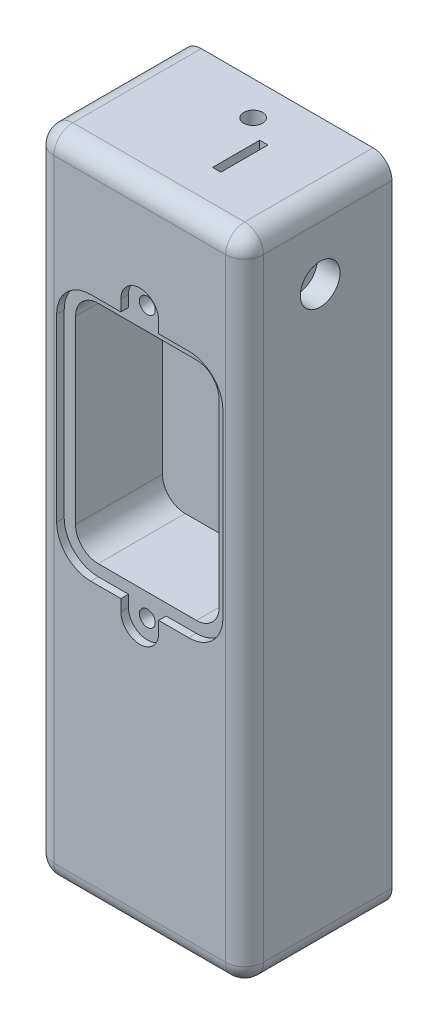
SolidWorks part; units mm, degrees
ref_plane "Plan de face" through (0, 0, 0) normal (0, 0, 1) x (1, 0, 0)
ref_plane "Plan de dessus" through (0, 0, 0) normal (0, 1, 0) x (1, 0, 0)
ref_plane "Plan de droite" through (0, 0, 0) normal (1, 0, 0) x (0, 0, -1)
sketch "Esquisse1" plane through (0, 0, 0) normal (0, 0, 1) x (1, 0, 0)
  circle A0 centre (18.73, -67.83) radius 1.6 construction
  circle A1 centre (-19.02, -68.37) radius 1.6 construction
  circle A2 centre (-11.6, -21.435) radius 1.6 construction
  circle A4 centre (17.62, 68.04) radius 1.6 construction
  circle A5 centre (-18.88, 68.04) radius 1.6 construction
  circle A6 centre (18.73, -67.83) radius 1.6
  circle A7 centre (-19.02, -68.37) radius 1.6
  circle A8 centre (-11.6, -21.435) radius 1.6
  circle A10 centre (17.62, 68.04) radius 1.6
  circle A11 centre (-18.88, 68.04) radius 1.6
  circle A12 centre (-18.88, 68.04) radius 4
  circle A13 centre (17.62, 68.04) radius 4
  circle A15 centre (-11.6, -21.435) radius 4
  circle A16 centre (-19.02, -68.37) radius 4
  circle A17 centre (18.73, -67.83) radius 4
  dimension "D1" = 8
extrude "Boss.-Extru.1" add sketch "Esquisse1" along normal blind 25
sketch "Esquisse2" plane through (0, 0, 25) normal (0, 0, 1) x (1, 0, 0)
  line L0 (-22.74, 72.15) -> (-22.74, -72.15) construction
  line L1 (-27.74, 98.04) -> (27.74, 98.04)
  line L2 (-27.74, 98.04) -> (-27.74, -74.15)
  line L3 (-27.74, -74.15) -> (27.74, -74.15)
  line L4 (27.74, 98.04) -> (27.74, -74.15)
  line L5 (22.74, -72.15) -> (22.74, 72.15) construction
  line L6 (-22.74, -72.15) -> (22.74, -72.15) construction
  circle A0 centre (-18.88, 68.04) radius 4 construction
  dimension "D1" = 30
  dimension "D2" = 5
  dimension "D3" = 5
  dimension "D4" = 2
extrude "Boss.-Extru.2" add sketch "Esquisse2" along normal blind 5
fillet "Congé1" radius 5 4 edges at (-27.74, 98.04, 27.5) (27.74, -74.15, 27.5) (-27.74, -74.15, 27.5) (27.74, 98.04, 27.5)
sketch "Esquisse4" plane through (0, 0, 25) normal (0, 0, -1) x (-1, 0, 0)
  line L0 (24.74, -69.15) -> (24.74, 93.04)
  line L1 (22.74, 95.04) -> (-22.74, 95.04)
  line L2 (-24.74, 93.04) -> (-24.74, -69.15)
  line L3 (-22.74, -71.15) -> (22.74, -71.15)
  line L4 (27.74, -69.15) -> (27.74, 93.04)
  line L5 (22.74, 98.04) -> (-22.74, 98.04)
  line L6 (-27.74, 93.04) -> (-27.74, -69.15)
  line L7 (-22.74, -74.15) -> (22.74, -74.15)
  line L8 (27.74, -69.15) -> (27.74, 93.04)
  line L9 (22.74, 98.04) -> (-22.74, 98.04)
  line L10 (-27.74, 93.04) -> (-27.74, -69.15)
  line L11 (-22.74, -74.15) -> (22.74, -74.15)
  arc A0 (24.74, 93.04) -> (22.74, 95.04) centre (22.74, 93.04) ccw
  arc A1 (-22.74, 95.04) -> (-24.74, 93.04) centre (-22.74, 93.04) ccw
  arc A2 (-24.74, -69.15) -> (-22.74, -71.15) centre (-22.74, -69.15) ccw
  arc A3 (22.74, -71.15) -> (24.74, -69.15) centre (22.74, -69.15) ccw
  arc A4 (27.74, 93.04) -> (22.74, 98.04) centre (22.74, 93.04) ccw
  arc A5 (-22.74, 98.04) -> (-27.74, 93.04) centre (-22.74, 93.04) ccw
  arc A6 (-27.74, -69.15) -> (-22.74, -74.15) centre (-22.74, -69.15) ccw
  arc A7 (22.74, -74.15) -> (27.74, -69.15) centre (22.74, -69.15) ccw
  arc A8 (27.74, 93.04) -> (22.74, 98.04) centre (22.74, 93.04) ccw
  arc A9 (-22.74, 98.04) -> (-27.74, 93.04) centre (-22.74, 93.04) ccw
  arc A10 (-27.74, -69.15) -> (-22.74, -74.15) centre (-22.74, -69.15) ccw
  arc A11 (22.74, -74.15) -> (27.74, -69.15) centre (22.74, -69.15) ccw
  dimension "D1" = 0
  dimension "D2" = 3
extrude "Boss.-Extru.3" add sketch "Esquisse4" along normal blind 34
sketch "Esquisse5" plane through (0, 98.04, 0) normal (0, 1, 0) x (1, 0, 0)
  line L0 (0, -30) -> (0, 9) construction
  line L1 (22.74, -30) -> (-22.74, -30) construction
  line L2 (-22.74, 9) -> (22.74, 9) construction
  circle A2 centre (0, 0) radius 2.5
  dimension "D1" = 5
extrude "Enlèv. mat.-Extru.1" cut sketch "Esquisse5" against normal up to next
sketch "Esquisse6" plane through (0, 98.04, 0) normal (0, 1, 0) x (1, 0, 0)
  line L0 (-22.74, -10.5) -> (22.74, -10.5) construction
  line L37 (-22.74, 9) -> (-22.74, -30) construction
  line L38 (22.74, -30) -> (22.74, 9) construction
  line L40 (8.2, -16.75) -> (6, -16.75)
  line L41 (8.2, -16.75) -> (8.2, -4.25)
  line L42 (8.2, -4.25) -> (6, -4.25)
  line L43 (6, -16.75) -> (6, -4.25)
  line L44 (8.2, -16.75) -> (6, -4.25) construction
  line L45 (8.2, -4.25) -> (6, -16.75) construction
  point P12 (7.1, -10.5)
  dimension "D1" = 29.84
  dimension "D3" = 2.2
  dimension "D4" = 12.5
fillet "Congé2" radius 5 8 edges at (26.2755, 96.5755, 30) (27.74, 11.945, 30) (26.2755, -72.6855, 30) (0, -74.15, 30) (-26.2755, -72.6855, 30) (-27.74, 11.945, 30) (-26.2755, 96.5755, 30) (0, 98.04, 30)
sketch "Esquisse8" plane through (0, 0, 25) normal (0, 0, -1) x (-1, 0, 0)
  line L2 (22.74, 95.04) -> (-22.74, 95.04) construction
  line L3 (-24.74, 93.04) -> (-24.74, -69.15) construction
  line L6 (3.26, 95.04) -> (-22.74, 95.04)
  line L7 (-24.74, 93.04) -> (-24.74, 73.04)
  line L8 (-24.74, 73.04) -> (3.26, 73.04)
  line L9 (3.26, 95.04) -> (3.26, 73.04)
  arc A1 (-22.74, 95.04) -> (-24.74, 93.04) centre (-22.74, 93.04) ccw construction
  arc A3 (-22.74, 95.04) -> (-24.74, 93.04) centre (-22.74, 93.04) ccw
  dimension "D1" = 22
  dimension "D2" = 28
extrude "Boss.-Extru.9" add sketch "Esquisse8" along normal blind 30
sketch "Esquisse9" plane through (0, 95.04, 0) normal (0, 1, 0) x (1, 0, 0)
  circle A1 centre (0, 0) radius 2.5
  circle A2 centre (0, 0) radius 2.5
  dimension "D1" = 0
extrude "Enlèv. mat.-Extru.3" cut sketch "Esquisse9" against normal up to surface (22 mm away) up to face at (10.74, 73.04, 10)
sketch "Esquisse13" plane through (-3.26, 0, 0) normal (-1, 0, 0) x (0, 0, 1)
  line L0 (10, 73.04) -> (10, 95.04) construction
  line L1 (-5, 73.04) -> (25, 73.04) construction
  line L2 (-5, 95.04) -> (25, 95.04) construction
  circle A0 centre (10, 78.7725) radius 2.5
  dimension "D1" = 5
extrude "Enlèv. mat.-Extru.4" cut sketch "Esquisse13" against normal up to surface (31 mm away) up to face at (27.74, 11.945, 8)
sketch "Esquisse14" plane through (27.74, 0, 0) normal (1, 0, 0) x (0, 0, -1)
  circle A0 centre (-10, 78.7725) radius 5.25
  dimension "D1" = 10.5
extrude "Enlèv. mat.-Extru.5" cut sketch "Esquisse14" against normal blind 6
ref_plane "Plan2" through (0, 0, 5) normal (0, 0, -1) x (-1, 0, 0)
sketch "Esquisse15" plane through (0, 0, 5) normal (0, 0, -1) x (-1, 0, 0)
  line L0 (-24.74, 73.04) -> (-24.74, -69.15) construction
  line L1 (-24.74, 65.4347) -> (24.74, 65.4347)
  line L2 (-24.74, 65.4347) -> (-24.74, 3.5486)
  line L3 (-24.74, 3.5486) -> (24.74, 3.5486)
  line L4 (24.74, 65.4347) -> (24.74, 3.5486)
  line L5 (24.74, -69.15) -> (24.74, 93.04) construction
sketch "Esquisse16" plane through (0, 0, 30) normal (0, 0, 1) x (1, 0, 0)
  line L1 (19, 3.35) -> (-19, 3.35)
  line L2 (19, 3.35) -> (19, 63.04)
  line L3 (19, 63.04) -> (-19, 63.04)
  line L4 (-19, 3.35) -> (-19, 63.04)
  line L5 (19, 3.35) -> (-19, 63.04) construction
  line L6 (19, 63.04) -> (-19, 3.35) construction
  line L7 (0, -21.45) -> (0, 21.45) construction
  line L10 (-22.74, 95.04) -> (22.74, 95.04) construction
  line L11 (16.4989, -71.15) -> (-16.144, -71.15) construction
  point P0 (0, 33.195)
  dimension "D1" = 38
  dimension "D2" = 32
  dimension "D3" = 74.5
extrude "Enlèv. mat.-Extru.6" cut sketch "Esquisse16" against normal up to surface (5 mm away) up to face at (-14.88, 68.04, 25)
fillet "Congé3" radius 6 4 edges at (-19, 3.35, 27.5) (19, 3.35, 27.5) (19, 63.04, 27.5) (-19, 63.04, 27.5)
sketch "Esquisse18" plane through (0, 0, 30) normal (0, 0, 1) x (1, 0, 0)
  line L8 (22, 9.35) -> (22, 57.04)
  line L9 (-13, 0.35) -> (13, 0.35)
  line L10 (-22, 57.04) -> (-22, 9.35)
  line L11 (13, 66.04) -> (-13, 66.04)
  line L12 (22, 9.35) -> (22, 57.04)
  line L13 (-13, 0.35) -> (13, 0.35)
  line L14 (-22, 57.04) -> (-22, 9.35)
  line L15 (13, 66.04) -> (-13, 66.04)
  arc A8 (13, 0.35) -> (22, 9.35) centre (13, 9.35) ccw
  arc A9 (-22, 9.35) -> (-13, 0.35) centre (-13, 9.35) ccw
  arc A10 (-13, 66.04) -> (-22, 57.04) centre (-13, 57.04) ccw
  arc A11 (22, 57.04) -> (13, 66.04) centre (13, 57.04) ccw
  arc A12 (13, 0.35) -> (22, 9.35) centre (13, 9.35) ccw
  arc A13 (-22, 9.35) -> (-13, 0.35) centre (-13, 9.35) ccw
  arc A14 (-13, 66.04) -> (-22, 57.04) centre (-13, 57.04) ccw
  arc A15 (22, 57.04) -> (13, 66.04) centre (13, 57.04) ccw
  dimension "D1" = 3
extrude "Enlèv. mat.-Extru.7" cut sketch "Esquisse18" against normal blind 2
sketch "Esquisse20" plane through (0, 0, 28) normal (0, 0, 1) x (1, 0, 0)
  line L0 (0, 77.7412) -> (0, -21.3772) construction
  line L1 (0, 69.04) -> (0, 63.04) construction
  line L2 (5, 69.04) -> (5, 63.04)
  line L3 (-5, 69.04) -> (-5, 63.04)
  line L4 (13, 66.04) -> (-13, 66.04) construction
  line L5 (0, 3.35) -> (0, -2.65) construction
  line L6 (5, 3.35) -> (5, -2.65)
  line L7 (-5, 3.35) -> (-5, -2.65)
  line L9 (-13, 0.35) -> (13, 0.35) construction
  arc A0 (5, 69.04) -> (-5, 69.04) centre (0, 69.04) ccw
  arc A1 (-5, 63.04) -> (5, 63.04) centre (0, 63.04) ccw
  arc A2 (5, 3.35) -> (-5, 3.35) centre (0, 3.35) ccw
  arc A3 (-5, -2.65) -> (5, -2.65) centre (0, -2.65) ccw
  point P5 (0, 66.04)
  point P14 (0, 0.35)
  dimension "D1" = 5
  dimension "D2" = 3
  dimension "D4" = 5
  dimension "D3" = 3
extrude "Enlèv. mat.-Extru.8" cut sketch "Esquisse20" along normal up to surface (2 mm away) up to face at (0, 33.195, 30)
sketch "Esquisse21" plane through (0, 0, 25) normal (0, 0, -1) x (-1, 0, 0)
  circle A0 centre (0, 69.04) radius 4.5
  circle A1 centre (0, -2.65) radius 4.5
  dimension "D1" = 9
extrude "Boss.-Extru.13" add sketch "Esquisse21" along normal blind 10
sketch "Esquisse22" plane through (0, 0, 28) normal (0, 0, 1) x (1, 0, 0)
  circle A0 centre (0, 69.04) radius 2.1
  circle A1 centre (0, -2.65) radius 2.1
  dimension "D1" = 4.2
extrude "Enlèv. mat.-Extru.9" cut sketch "Esquisse22" against normal blind 8
sketch "Esquisse23" plane through (0, -74.15, 0) normal (0, -1, 0) x (1, 0, 0)
  line L0 (4.002, 3.65) -> (-4.698, 8.35) construction
  line L1 (22.74, 25) -> (-22.74, 25) construction
  line L3 (4.002, 3.65) -> (-5.019, 3.65)
  line L7 (4.323, 8.35) -> (4.002, 3.65)
  line L13 (-4.698, 8.35) -> (4.323, 8.35)
  line L15 (-5.019, 3.65) -> (-4.698, 8.35)
  point P2 (-0.348, 6)
  dimension "D1" = 4.7
  dimension "D2" = 9
  dimension "D3" = 19
extrude "Enlèv. mat.-Extru.10" cut sketch "Esquisse23" against normal up to next
fillet "Congé4" radius 1.5 4 edges at (-5.019, -72.65, 3.65) (4.002, -72.65, 3.65) (4.323, -72.65, 8.35) (-4.698, -72.65, 8.35)
sketch "Esquisse24" plane through (0, -74.15, 0) normal (0, -1, 0) x (1, 0, 0)
  line L0 (0, 25) -> (0, -9) construction
  line L1 (22.74, 25) -> (-22.74, 25) construction
  line L2 (22.74, -9) -> (-22.74, -9) construction
  line L4 (6.7, 21.35) -> (-6.7, 21.35)
  line L5 (6.7, 21.35) -> (6.7, 12.65)
  line L6 (6.7, 12.65) -> (-6.7, 12.65)
  line L7 (-6.7, 21.35) -> (-6.7, 12.65)
  line L8 (6.7, 21.35) -> (-6.7, 12.65) construction
  line L9 (6.7, 12.65) -> (-6.7, 21.35) construction
  point P6 (0, 17)
  dimension "D1" = 13.4
  dimension "D2" = 8.7
  dimension "D3" = 8
extrude "Enlèv. mat.-Extru.11" cut sketch "Esquisse24" against normal up to next
sketch "Esquisse26" plane through (0, -74.15, 0) normal (0, -1, 0) x (1, 0, 0)
  line L0 (-6.7, 21.35) -> (6.7, 12.65) construction
  line L2 (7.5, 11.8) -> (-7.5, 11.8)
  line L3 (7.5, 11.8) -> (7.5, 22.2)
  line L4 (7.5, 22.2) -> (-7.5, 22.2)
  line L5 (-7.5, 11.8) -> (-7.5, 22.2)
  line L6 (7.5, 11.8) -> (-7.5, 22.2) construction
  line L7 (7.5, 22.2) -> (-7.5, 11.8) construction
  point P4 (0, 17)
  dimension "D1" = 10.4
  dimension "D2" = 15
extrude "Enlèv. mat.-Extru.12" cut sketch "Esquisse26" against normal blind 1.8
sketch "Esquisse27" plane through (0, 0, 25) normal (0, 0, -1) x (-1, 0, 0)
  line L0 (-13, 1.35) -> (13, 1.35)
  line L1 (21, 9.35) -> (21, 57.04)
  line L2 (13, 65.04) -> (-13, 65.04)
  line L3 (-21, 57.04) -> (-21, 9.35)
  line L4 (-13, 3.35) -> (13, 3.35)
  line L5 (19, 9.35) -> (19, 57.04)
  line L6 (13, 63.04) -> (-13, 63.04)
  line L7 (-19, 57.04) -> (-19, 9.35)
  line L8 (-13, 3.35) -> (13, 3.35)
  line L9 (19, 9.35) -> (19, 57.04)
  line L10 (13, 63.04) -> (-13, 63.04)
  line L11 (-19, 57.04) -> (-19, 9.35)
  arc A0 (13, 1.35) -> (21, 9.35) centre (13, 9.35) ccw
  arc A1 (21, 57.04) -> (13, 65.04) centre (13, 57.04) ccw
  arc A2 (-13, 65.04) -> (-21, 57.04) centre (-13, 57.04) ccw
  arc A3 (-21, 9.35) -> (-13, 1.35) centre (-13, 9.35) ccw
  arc A4 (13, 3.35) -> (19, 9.35) centre (13, 9.35) ccw
  arc A5 (19, 57.04) -> (13, 63.04) centre (13, 57.04) ccw
  arc A6 (-13, 63.04) -> (-19, 57.04) centre (-13, 57.04) ccw
  arc A7 (-19, 9.35) -> (-13, 3.35) centre (-13, 9.35) ccw
  arc A8 (13, 3.35) -> (19, 9.35) centre (13, 9.35) ccw
  arc A9 (19, 57.04) -> (13, 63.04) centre (13, 57.04) ccw
  arc A10 (-13, 63.04) -> (-19, 57.04) centre (-13, 57.04) ccw
  arc A11 (-19, 9.35) -> (-13, 3.35) centre (-13, 9.35) ccw
  dimension "D1" = 0
  dimension "D2" = 2
extrude "Boss.-Extru.19" add sketch "Esquisse27" along normal blind 20
sketch "Esquisse28" plane through (0, 0, 5) normal (0, 0, -1) x (-1, 0, 0)
  line L4 (-21, 57.04) -> (-21, 9.35)
  line L5 (-13, 1.35) -> (13, 1.35)
  line L6 (21, 9.35) -> (21, 57.04)
  line L7 (13, 65.04) -> (-13, 65.04)
  line L8 (-21, 57.04) -> (-21, 9.35)
  line L9 (-13, 1.35) -> (13, 1.35)
  line L10 (21, 9.35) -> (21, 57.04)
  line L11 (13, 65.04) -> (-13, 65.04)
  arc A6 (-16.6478, 64.1599) -> (-15.5301, 64.6294) centre (-17.62, 68.04) ccw
  arc A7 (-16.6478, 64.1599) -> (-21, 57.04) centre (-13, 57.04) ccw
  arc A8 (-21, 9.35) -> (-13, 1.35) centre (-13, 9.35) ccw
  arc A9 (13, 1.35) -> (21, 9.35) centre (13, 9.35) ccw
  arc A10 (21, 57.04) -> (13, 65.04) centre (13, 57.04) ccw
  arc A11 (-13, 65.04) -> (-15.5301, 64.6294) centre (-13, 57.04) ccw
  arc A12 (-16.6478, 64.1599) -> (-15.5301, 64.6294) centre (-17.62, 68.04) ccw
  arc A13 (-16.6478, 64.1599) -> (-21, 57.04) centre (-13, 57.04) ccw
  arc A14 (-21, 9.35) -> (-13, 1.35) centre (-13, 9.35) ccw
  arc A15 (13, 1.35) -> (21, 9.35) centre (13, 9.35) ccw
  arc A16 (21, 57.04) -> (13, 65.04) centre (13, 57.04) ccw
  arc A17 (-13, 65.04) -> (-15.5301, 64.6294) centre (-13, 57.04) ccw
  dimension "D1" = 0
extrude "Boss.-Extru.20" add sketch "Esquisse28" along normal blind 2
sketch "Esquisse29" plane through (0, 1.35, 0) normal (0, -1, 0) x (1, 0, 0)
  line L0 (13, 14) -> (-13, 14) construction
  line L1 (13, 3) -> (13, 25) construction
  line L2 (-13, 3) -> (-13, 25) construction
  circle A0 centre (10.9512, 14) radius 2
  dimension "D1" = 4
extrude "Enlèv. mat.-Extru.13" cut sketch "Esquisse29" against normal up to next
extrude "Enlèv. mat.-Extru.14" cut sketch "Esquisse6" against normal up to next
sketch "Esquisse30" plane through (0, -74.15, 0) normal (0, -1, 0) x (1, 0, 0)
  line L8 (-3.413, 1.65) -> (2.6009, 1.65)
  line L9 (6.0928, 4.9115) -> (6.2089, 6.6115)
  line L10 (2.717, 10.35) -> (-3.2969, 10.35)
  line L11 (-6.7888, 7.0885) -> (-6.9049, 5.3885)
  line L12 (-3.413, 1.65) -> (2.6009, 1.65)
  line L13 (6.0928, 4.9115) -> (6.2089, 6.6115)
  line L14 (2.717, 10.35) -> (-3.2969, 10.35)
  line L15 (-6.7888, 7.0885) -> (-6.9049, 5.3885)
  arc A8 (-6.9049, 5.3885) -> (-3.413, 1.65) centre (-3.413, 5.15) ccw
  arc A9 (2.6009, 1.65) -> (6.0928, 4.9115) centre (2.6009, 5.15) ccw
  arc A10 (6.2089, 6.6115) -> (2.717, 10.35) centre (2.717, 6.85) ccw
  arc A11 (-3.2969, 10.35) -> (-6.7888, 7.0885) centre (-3.2969, 6.85) ccw
  arc A12 (-6.9049, 5.3885) -> (-3.413, 1.65) centre (-3.413, 5.15) ccw
  arc A13 (2.6009, 1.65) -> (6.0928, 4.9115) centre (2.6009, 5.15) ccw
  arc A14 (6.2089, 6.6115) -> (2.717, 10.35) centre (2.717, 6.85) ccw
  arc A15 (-3.2969, 10.35) -> (-6.7888, 7.0885) centre (-3.2969, 6.85) ccw
  dimension "D1" = 2
extrude "Enlèv. mat.-Extru.15" cut sketch "Esquisse30" against normal blind 1.5
